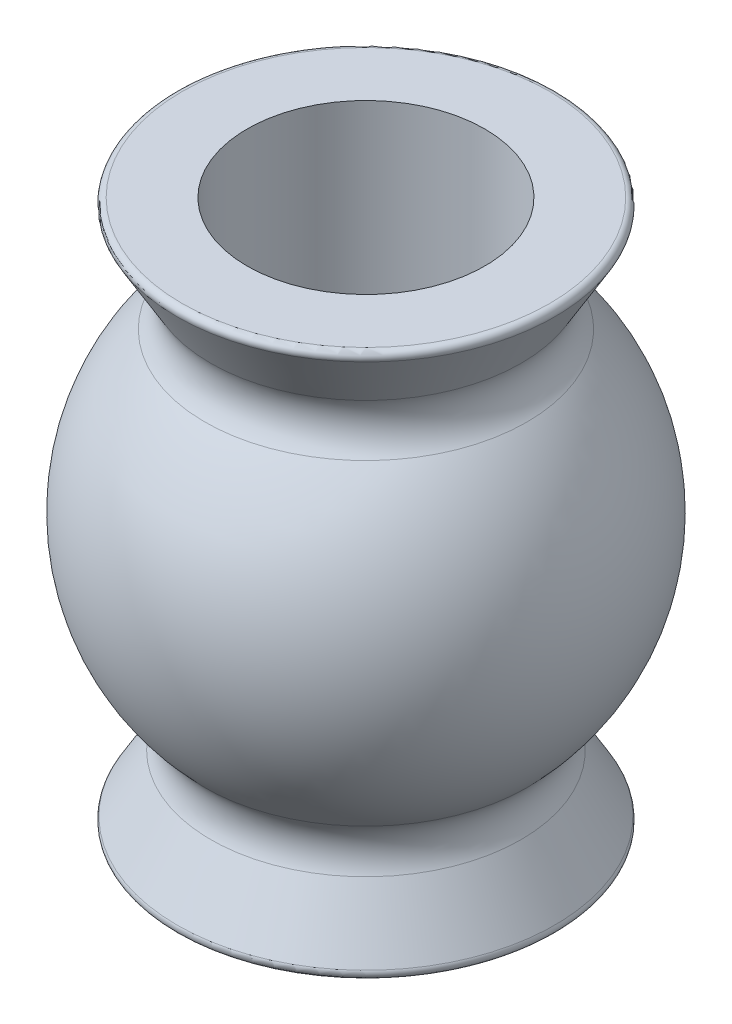
SolidWorks part; units mm, degrees
ref_plane "Front Plane" through (0, 0, 0) normal (0, 0, 1) x (1, 0, 0)
ref_plane "Top Plane" through (0, 0, 0) normal (0, 1, 0) x (1, 0, 0)
ref_plane "Right Plane" through (0, 0, 0) normal (1, 0, 0) x (0, 0, -1)
sketch "Sketch1" plane through (0, 0, 0) normal (0, 0, 1) x (1, 0, 0)
  line L0 (1.524, 0) -> (1.524, 6.985)
  line L1 (1.524, 6.985) -> (2.4892, 6.985)
  line L2 (2.4892, 6.985) -> (1.7773, 5.7785)
  line L3 (1.7773, 1.2065) -> (2.4892, 0)
  line L4 (2.4892, 0) -> (1.524, 0)
  line L5 (0, 0) -> (0, 7.7819) construction
  arc A0 (1.7773, 5.7785) -> (1.7773, 1.2065) centre (0, 3.4925) cw
  point P10 (1.524, 3.4925)
  dimension "D3" = 2.8956
  dimension "D1" = 3.048
  dimension "D2" = 6.985
  dimension "D4" = 4.9784
  dimension "D5" = 4.572
  dimension "D6" = 0.7969
revolve "Revolve1" add sketch "Sketch1" angle 360 about L5
fillet "Fillet1" radius 0.508 2 edges at (0, 1.2065, -1.7773) (0, 5.7785, -1.7773)
fillet "Fillet2" radius 0.0762 2 edges at (0, 0, -2.4892) (0, 6.985, -2.4892)
